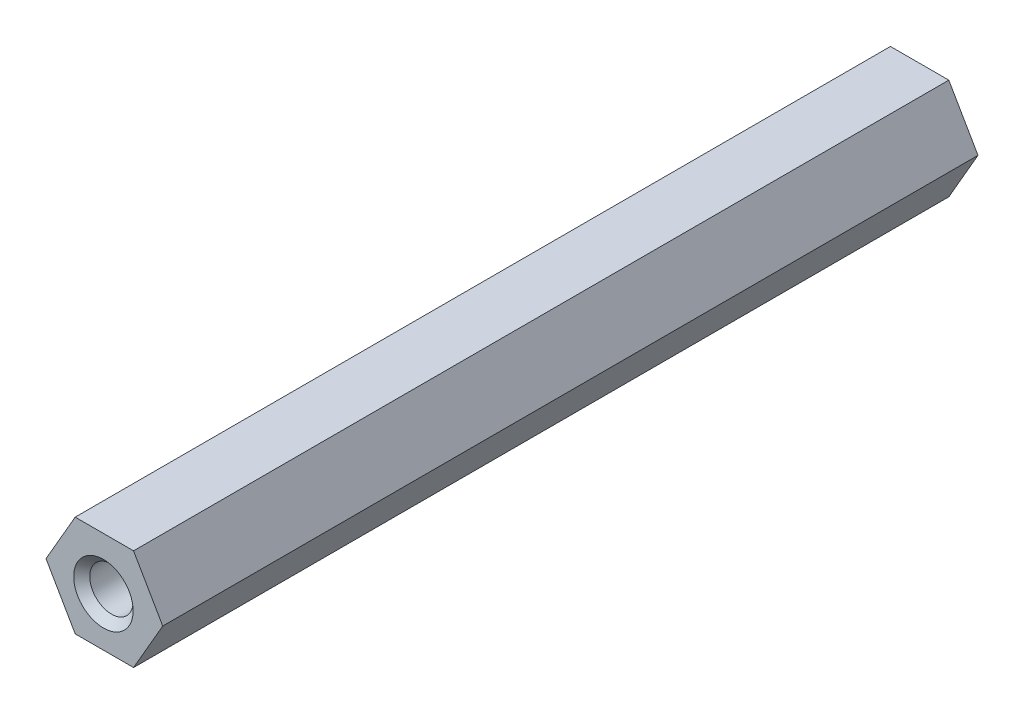
SolidWorks part; units mm, degrees
other "Defeature"
material "6061 Alloy"
ref_plane "Front Plane" through (0, 0, 0) normal (0, 0, 1) x (1, 0, 0)
ref_plane "Top Plane" through (0, 0, 0) normal (0, 1, 0) x (1, 0, 0)
ref_plane "Right Plane" through (0, 0, 0) normal (1, 0, 0) x (0, 0, -1)
sketch "Sketch1" plane through (0, 0, 0) normal (0, 0, 1) x (1, 0, 0)
  line L1 (3.6373, 0) -> (1.8187, 3.15)
  line L2 (1.8187, 3.15) -> (-1.8187, 3.15)
  line L3 (-1.8187, 3.15) -> (-3.6373, 0)
  line L4 (-3.6373, 0) -> (-1.8187, -3.15)
  line L5 (-1.8187, -3.15) -> (1.8187, -3.15)
  line L6 (1.8187, -3.15) -> (3.6373, 0)
  circle A0 centre (0, 0) radius 3.15 construction
  dimension "D1" = 6.3
extrude "Boss-Extrude1" add sketch "Sketch1" against normal mid plane 50.8
hole_wizard "#6-32 Tapped Hole8" positions "3DSketch13" profile "Sketch27" tap size "#6-32" standard "Ansi Inch" end condition through all
sketch3d "3DSketch13"
  point P0 (-0.0588, -0.1018, 25.4)
  dimension "D1" = 3.58
  dimension "D2" = 3.58
sketch "Sketch27" plane through (-0.0588, -0.1018, 25.4) normal (1, 0, 0) x (0, -1, 0)
  line L0 (0, 0) -> (0, 50.8)
  line L1 (0, 50.8) -> (1.3525, 50.8)
  line L2 (1.3525, 50.8) -> (1.3525, 0)
  line L5 (1.3525, 0) -> (0, 0)
  line L11 (0, -6.35) -> (0, 107.95) construction
  dimension "Thru Tap Drill Dia." = 2.7051
  dimension "Thru Tap Drill Depth" = 50.8
cosmetic thread "Hole Thread12" parameters "D2"=3.5052
chamfer "Chamfer1" distance 0.5 angle 45 1 edges at (1.2938, -0.1018, 25.4)
chamfer "Chamfer2" distance 0.5 angle 45 1 edges at (1.2938, -0.1018, -25.4)
sketch "Sketch15" plane through (0, 0, 25.4) normal (0, 0, 1) x (1, 0, 0)
  circle A0 centre (0, 0) radius 1.5
  dimension "D1" = 3
extrude "Cut-Extrude1" [suppressed] cut sketch "Sketch15" against normal through all
